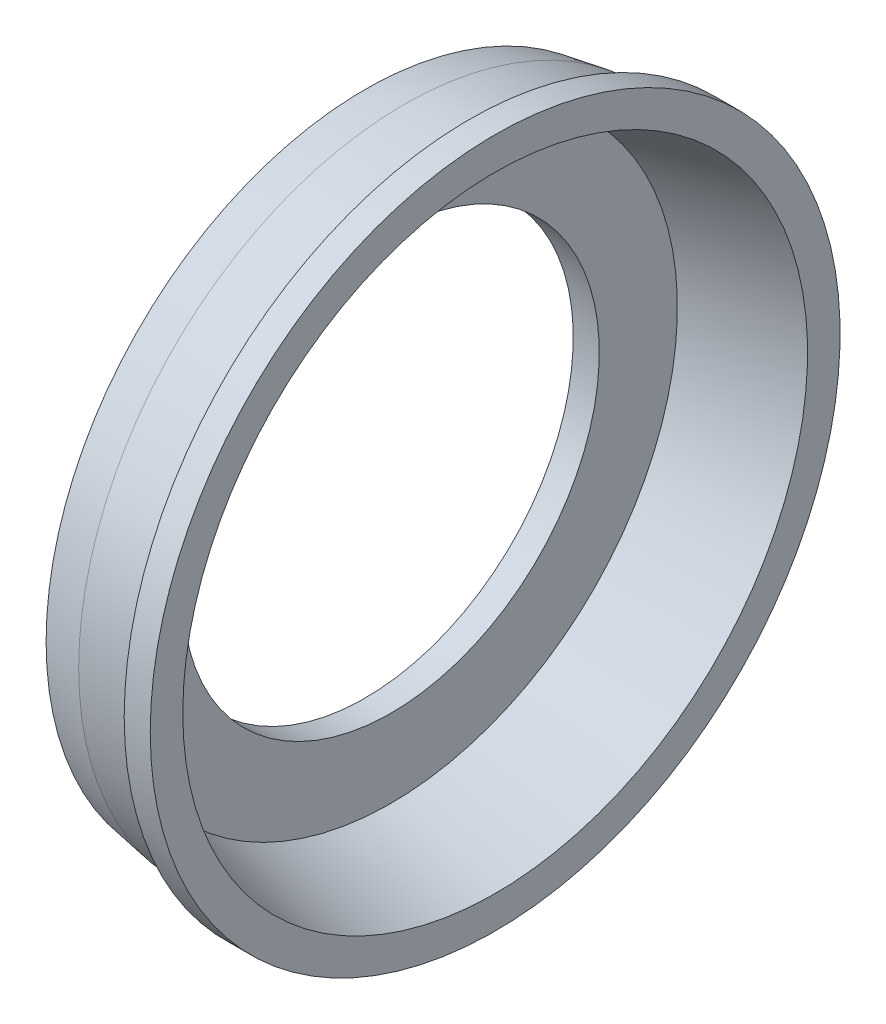
SolidWorks part; units mm, degrees
ref_plane "Płaszczyzna przednia" through (0, 0, 0) normal (0, 0, 1) x (1, 0, 0)
ref_plane "Płaszczyzna górna" through (0, 0, 0) normal (0, 1, 0) x (1, 0, 0)
ref_plane "Płaszczyzna prawa" through (0, 0, 0) normal (1, 0, 0) x (0, 0, -1)
sketch "Szkic1" plane through (0, 0, 0) normal (0, 0, 1) x (1, 0, 0)
  line L0 (0, 26.5) -> (2, 26.5)
  line L1 (2, 26.5) -> (2, 24)
  line L2 (2, 24) -> (-6, 22)
  line L3 (-6, 22) -> (-6, 16)
  line L4 (-6, 22) -> (-6, -22) construction
  line L5 (-6, 16) -> (-8, 16)
  line L6 (-8, 16) -> (-8, 25)
  line L7 (-8, 25) -> (0, 25)
  line L8 (0, 28) -> (0, -28) construction
  line L9 (0, 25) -> (0, 26.5)
  line L10 (-21.4485, 0) -> (33.2318, 0) construction
  dimension "D1" = 50
  dimension "D2" = 2
  dimension "D3" = 9
revolve "Obrót1" add sketch "Szkic1" angle 360 about L10
chamfer "Sfazowanie1" distance 3 distance2 0.5 1 edges at (-8, 0, 25)
